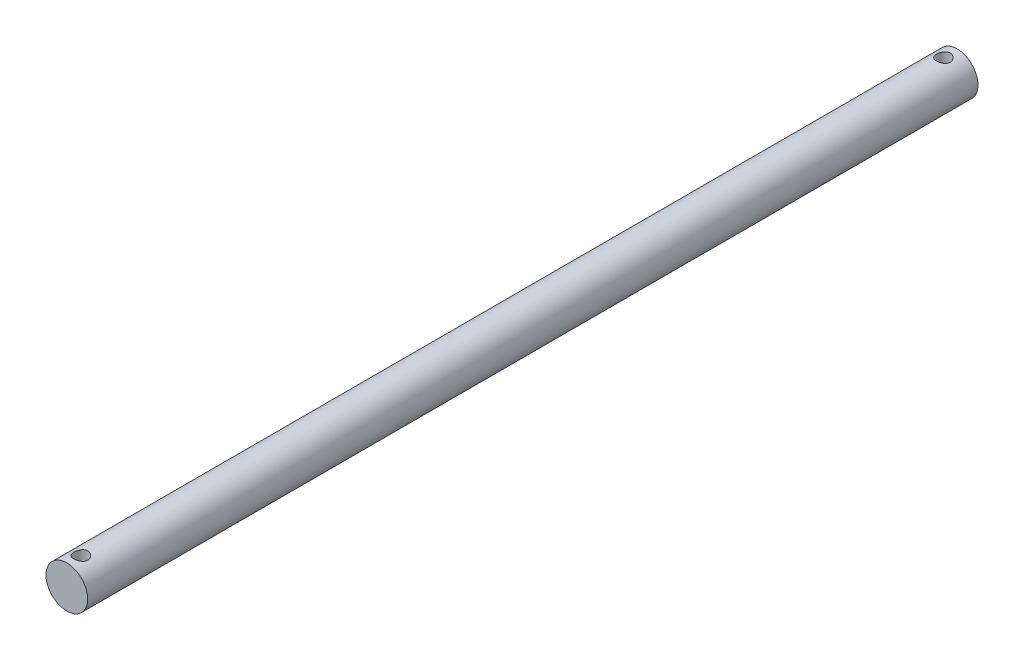
SolidWorks part; units mm, degrees
material "AISI 304"
ref_plane "Front" through (0, 0, 0) normal (0, 0, 1) x (1, 0, 0)
ref_plane "Top" through (0, 0, 0) normal (0, 1, 0) x (1, 0, 0)
ref_plane "Right" through (0, 0, 0) normal (1, 0, 0) x (0, 0, -1)
sketch "Sketch1" plane through (0, 0, 0) normal (0, 0, 1) x (1, 0, 0)
  circle A0 centre (0, 0) radius 4.7625
  dimension "D1" = 9.525
extrude "Boss-Extrude1" add sketch "Sketch1" along normal mid plane 203.2
sketch "Sketch2" plane through (0, 0, 0) normal (0, 1, 0) x (1, 0, 0)
  line L0 (4.7625, 101.6) -> (-4.7625, 101.6) construction
  circle A0 centre (0, 98.425) radius 1.5875
  dimension "D1" = 3.175
  dimension "D2" = 3.175
extrude "Split Ring Hole" cut sketch "Sketch2" against normal through all and the other way through all
mirror "Mirror1" about plane through (0, 0, 0) normal (0, 0, 1) of "Split Ring Hole"
